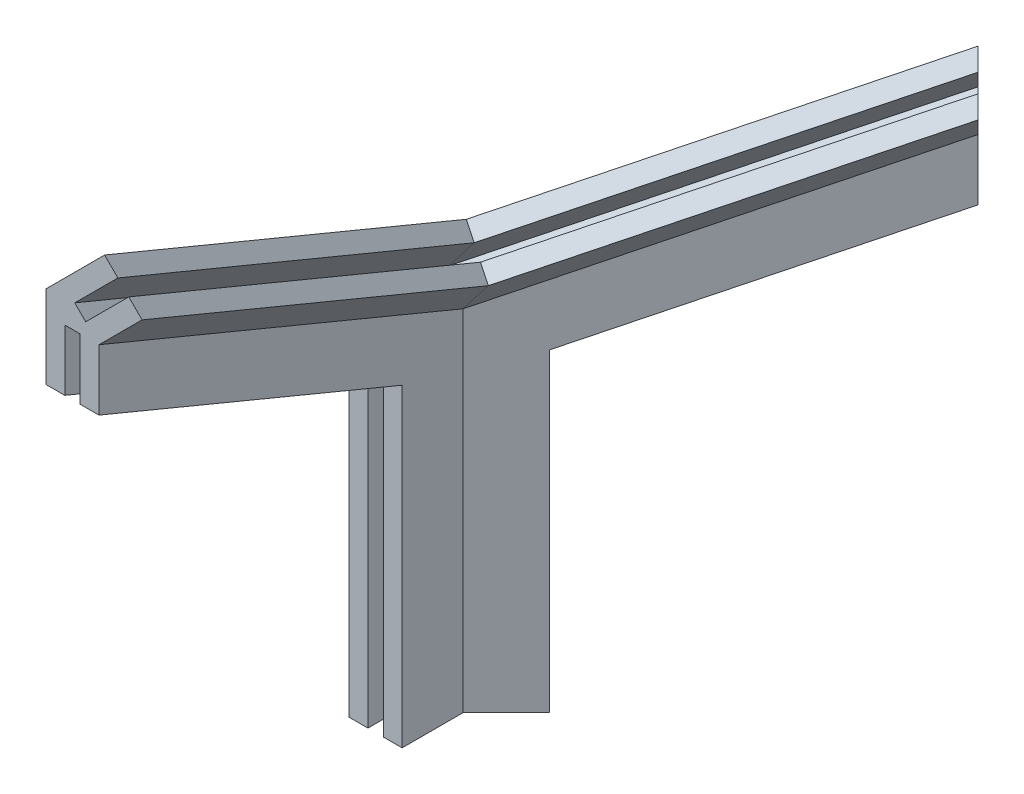
SolidWorks part; units mm, degrees
ref_plane "Front Plane" through (0, 0, 0) normal (0, 0, 1) x (1, 0, 0)
ref_plane "Top Plane" through (0, 0, 0) normal (0, 1, 0) x (1, 0, 0)
ref_plane "Right Plane" through (0, 0, 0) normal (1, 0, 0) x (0, 0, -1)
sketch "Sketch1" plane through (0, 0, 0) normal (0, 1, 0) x (1, 0, 0)
  line L0 (3.6221, 4.1978) -> (3.6221, -8.8022)
  line L1 (3.6221, -8.8022) -> (-0.3779, -8.8022)
  line L2 (-0.3779, -8.8022) -> (-0.3779, 4.1978)
  line L3 (-0.3779, 4.1978) -> (-3.6779, 4.1978)
  line L4 (-3.6779, 4.1978) -> (-3.6779, -8.8022)
  line L5 (-3.6779, -8.8022) -> (-7.6779, -8.8022)
  line L6 (-7.6779, -8.8022) -> (-7.6779, 8.8784)
  line L7 (3.6221, 4.1978) -> (-7.6779, 8.8784)
extrude "Boss-Extrude1" add sketch "Sketch1" along normal blind 80
sketch "Sketch2" plane through (-7.6779, 0, 0) normal (-1, 0, 0) x (0, 0, 1)
  line L2 (-8.8784, 80) -> (8.8022, 80)
  line L4 (8.8022, 80) -> (-8.8784, 72.6722)
  line L5 (-8.8784, 80) -> (-8.8784, 0) construction
  line L7 (-8.8784, 72.6722) -> (-8.8784, 80)
  line L8 (-8.8784, 80) -> (8.8022, 80)
  line M3 (8.8022, 80) -> (-8.8784, 80)
  line M4 (-8.8784, 80) -> (-8.8784, 0)
extrude "Cut-Extrude2" cut sketch "Sketch2" against normal through all contours L4 M3 M4
sketch "Sketch6" plane through (0, 0, 8.8022) normal (0, 0, 1) x (1, 0, 0)
  line L0 (-7.6779, 80) -> (-7.6779, 67)
  line L1 (-7.6779, 80) -> (-7.6779, 0) construction
  line L2 (-7.6779, 67) -> (-3.6779, 67)
  line L3 (-3.6779, 80) -> (-3.6779, 0) construction
  line L4 (-3.6779, 67) -> (-3.6779, 80)
  line L5 (-3.6779, 80) -> (-7.6779, 80)
  line L6 (-0.3779, 80) -> (-0.3779, 67)
  line L7 (-0.3779, 80) -> (-0.3779, 0) construction
  line L8 (-0.3779, 67) -> (3.6221, 67)
  line L9 (3.6221, 80) -> (3.6221, 0) construction
  line L10 (3.6221, 67) -> (3.6221, 80)
  line L11 (3.6221, 80) -> (-0.3779, 80)
extrude "Boss-Extrude6" add sketch "Sketch6" along direction (0, -0.3829, -0.9238) on the side of the normal blind 70
sketch "Sketch7" plane through (0, 0, 73.4683) normal (0, 0, 1) x (1, 0, 0)
  line L0 (3.6221, 106.801) -> (-7.6779, 106.801)
  line L1 (3.6221, 106.801) -> (-7.6779, 111.4816)
  line L2 (-7.6779, 106.801) -> (-7.6779, 111.4816)
  point P4 (0, 0)
  point P7 (-7.9142, 111.4816)
ref_plane "Plane2" through (2.0146, 0, -4.8637) normal (0.3827, 0, -0.9239) x (-0.9239, 0, -0.3827)
extrude "Boss-Extrude7" add sketch "Sketch7" along direction (0, -0.3829, -0.9238) on the side against the normal up to surface (89.139 mm away) up to plane "Plane2"
ref_plane "Plane3" through (24.0054, 57.9541, -24.0192) normal (0.3574, 0.8628, -0.3576) x (0.934, -0.3301, 0.1368)
sketch "Sketch14" plane through (0, 0, 73.4683) normal (0, 0, 1) x (1, 0, 0)
  line L0 (7.6526, 121.1553) -> (4.8242, 123.9837)
  line L1 (3.6221, 106.801) -> (12.8145, 115.9934)
  line L2 (12.8145, 115.9934) -> (9.986, 118.8218)
  line L3 (9.986, 118.8218) -> (0.7936, 109.6294)
  line L4 (0.7936, 109.6294) -> (-1.5398, 111.9629)
  line L5 (-1.5398, 111.9629) -> (7.6526, 121.1553)
  line L6 (4.8242, 123.9837) -> (-7.6779, 111.4816)
  line L7 (-7.6779, 111.4816) -> (3.6221, 106.801)
extrude "Boss-Extrude8" add sketch "Sketch14" along direction (0, 0.3829, 0.9238) on the side against the normal up to surface (82.2651 mm away) up to plane "Plane2"
mirror "Mirror9" about plane through (2.0146, 0, -4.8637) normal (0.3827, 0, -0.9239) of bodies 110
